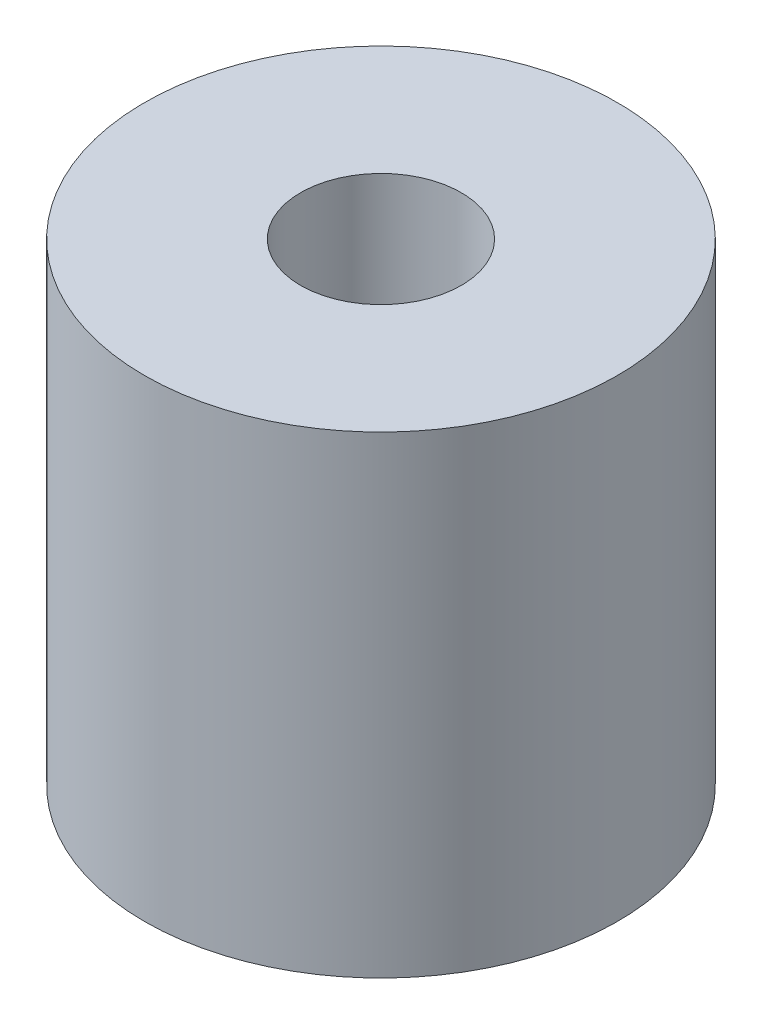
SolidWorks part; units mm, degrees
ref_plane "Front Plane" through (0, 0, 0) normal (0, 0, 1) x (1, 0, 0)
ref_plane "Top Plane" through (0, 0, 0) normal (0, 1, 0) x (1, 0, 0)
ref_plane "Right Plane" through (0, 0, 0) normal (1, 0, 0) x (0, 0, -1)
sketch "Sketch1" plane through (0, 0, 0) normal (0, 1, 0) x (1, 0, 0)
  circle A0 centre (0, 0) radius 1.7
  circle A1 centre (0, 0) radius 5
  dimension "D1" = 3.4
  dimension "D2" = 10
extrude "Boss-Extrude1" add sketch "Sketch1" along normal blind 10
